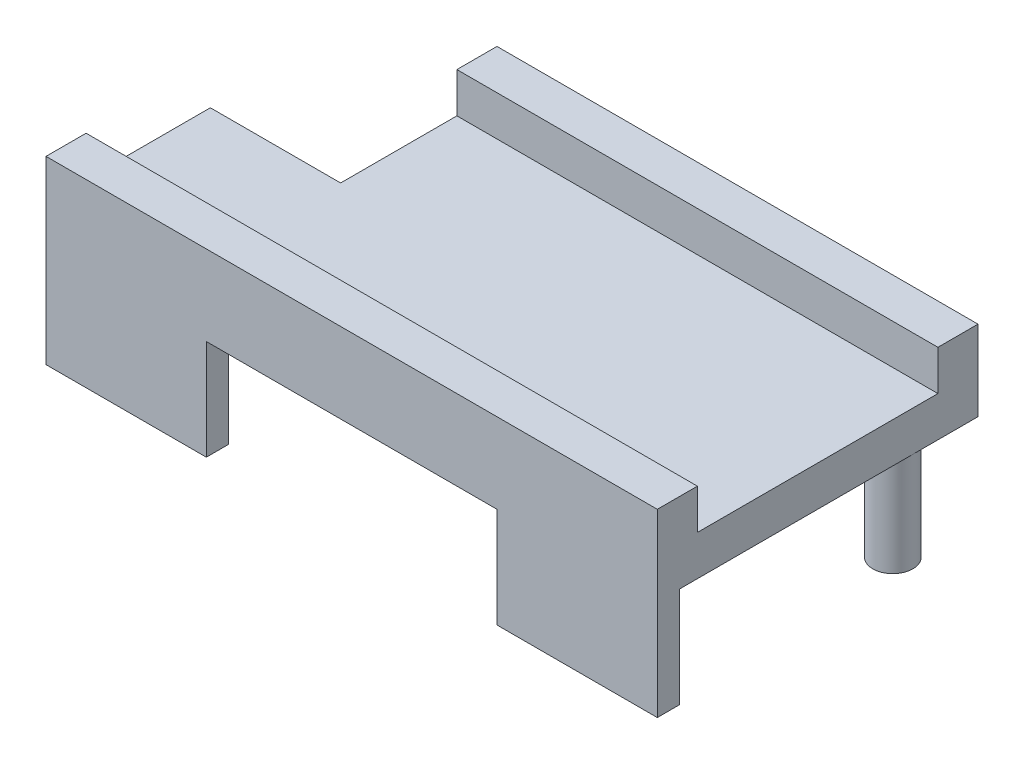
SolidWorks part; units mm, degrees
ref_plane "Ebene vorne" through (0, 0, 0) normal (0, 0, 1) x (1, 0, 0)
ref_plane "Ebene oben" through (0, 0, 0) normal (0, 1, 0) x (1, 0, 0)
ref_plane "Ebene rechts" through (0, 0, 0) normal (1, 0, 0) x (0, 0, -1)
sketch "Sketch1" plane through (0, 0, 0) normal (0, 1, 0) x (1, 0, 0)
  line L1 (-15.25, 8) -> (15.25, 8)
  line L2 (-15.25, 8) -> (-15.25, -8)
  line L3 (-15.25, -8) -> (15.25, -8)
  line L4 (15.25, 8) -> (15.25, -8)
  line L5 (-15.25, 8) -> (15.25, -8) construction
  line L6 (-15.25, -8) -> (15.25, 8) construction
  point P0 (0, 0)
  dimension "D1" = 16
  dimension "D2" = 30.5
extrude "Boss-Extrude1" add sketch "Sketch1" along normal blind 2
sketch "Sketch3" plane through (0, 0, 0) normal (0, 1, 0) x (1, 0, 0)
  line L0 (-9.3, 6.9) -> (-9.3, 2.7) construction
  line L1 (-15.7, 6.9) -> (-9.3, 6.9) construction
  line L2 (-15.7, 6.9) -> (-15.7, -6.9) construction
  line L3 (-15.7, -6.9) -> (15.7, -6.9) construction
  line L4 (15.7, 2.7) -> (15.7, -6.9) construction
  line L5 (-15.25, 8) -> (-15.25, -8) construction
  line L7 (-9.3, 2.7) -> (15.7, 2.7) construction
  line L11 (15.25, 8) -> (-15.25, 8) construction
  line L12 (-5.7, 8) -> (-2.8, 8)
  line L13 (-15.25, -8) -> (-7.25, -8)
  line L14 (-15.25, -8) -> (-15.25, -6.9)
  line L15 (-15.25, -6.9) -> (-7.25, -6.9)
  line L16 (-7.25, -8) -> (-7.25, -6.9)
  line L17 (15.25, -8) -> (7.25, -8)
  line L18 (15.25, -8) -> (15.25, -6.9)
  line L19 (15.25, -6.9) -> (7.25, -6.9)
  line L20 (7.25, -8) -> (7.25, -6.9)
  line L21 (-5.7, 8) -> (-5.7, 5.2)
  line L22 (-5.7, 5.2) -> (-2.8, 5.2)
  line L23 (-2.8, 8) -> (-2.8, 5.2)
  circle A0 centre (14.2, 4.8) radius 1
  point P0 (0, 0)
  point P4 (-15.25, 6.9)
  dimension "D5" = 2
  dimension "D1" = 13.8
  dimension "D2" = 31.4
  dimension "D3" = 25
  dimension "D4" = 9.6
  dimension "D6" = 1.1
  dimension "D7" = 8
  dimension "D8" = 8
  dimension "D9" = 1.1
  dimension "D12" = 9.55
  dimension "D13" = 2.9
  dimension "D14" = 2.8
extrude "Boss-Extrude3" add sketch "Sketch3" against normal blind 8
sketch "Sketch4" plane through (0, 0, 0) normal (0, 1, 0) x (1, 0, 0)
  line L0 (-15.25, 2.7) -> (-15.25, 8)
  line L2 (-15.25, 2.7) -> (-15.25, 0.2)
  line L3 (-15.25, 0.2) -> (-8.75, 0.2)
  line L4 (-8.75, 2.7) -> (-8.75, 0.2)
  line L11 (15.25, 8) -> (-15.25, 8) construction
  line L12 (-15.25, 8) -> (-8.75, 8)
  line L13 (-8.75, 8) -> (-8.75, 2.7)
  dimension "D1" = 6.5
extrude "Cut-Extrude2" cut sketch "Sketch4" along normal blind 10
sketch "Sketch5" plane through (0, -8, 0) normal (0, -1, 0) x (1, 0, 0)
  line L1 (-15.25, 8) -> (15.25, 8)
  line L2 (-15.25, 8) -> (-15.25, 6.9)
  line L3 (-15.25, 6.9) -> (15.25, 6.9)
  line L4 (15.25, 8) -> (15.25, 6.9)
  circle A0 centre (14.2, -4.8) radius 1
extrude "Cut-Extrude3" cut sketch "Sketch5" against normal blind 3
sketch "Sketch6" plane through (0, 2, 0) normal (0, 1, 0) x (1, 0, 0)
  line L0 (15.25, 8) -> (-8.75, 8) construction
  line L1 (15.25, -8) -> (-15.25, -8)
  line L2 (15.25, -8) -> (15.25, -6)
  line L3 (15.25, 8) -> (-8.75, 8)
  line L4 (-15.25, -8) -> (-15.25, -6)
  line L5 (-15.25, 0.2) -> (-15.25, -8) construction
  line L7 (-8.75, 6) -> (15.25, 6)
  line L9 (-15.25, -6) -> (15.25, -6)
  line L11 (15.25, 6) -> (15.25, 8)
  line L12 (-8.75, 8) -> (-8.75, 6)
  line L13 (-8.75, 8) -> (-8.75, 0.2) construction
  dimension "D1" = 2
  dimension "D2" = 2
extrude "Boss-Extrude4" add sketch "Sketch6" along normal blind 2
